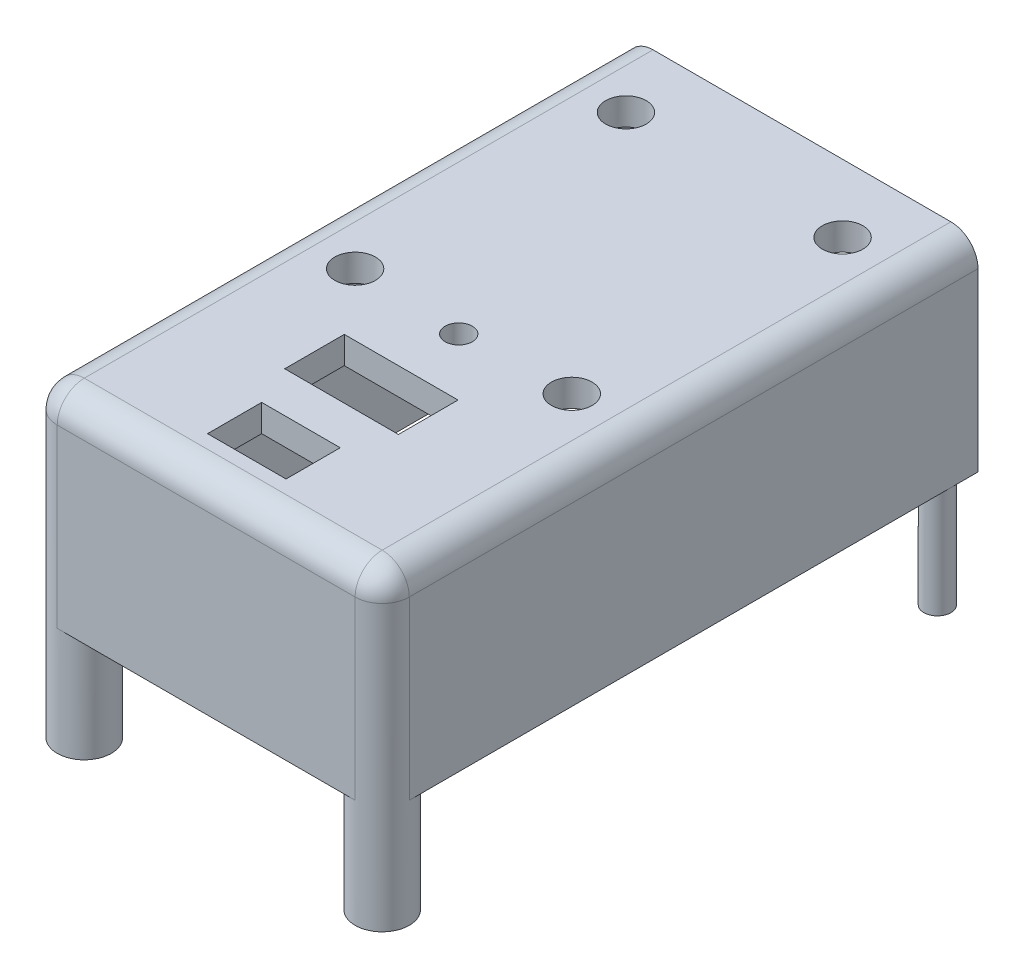
SolidWorks part; units mm, degrees
ref_plane "Front Plane" through (0, 0, 0) normal (0, 0, 1) x (1, 0, 0)
ref_plane "Top Plane" through (0, 0, 0) normal (0, 1, 0) x (1, 0, 0)
ref_plane "Right Plane" through (0, 0, 0) normal (1, 0, 0) x (0, 0, -1)
sketch "Sketch1" plane through (0, 0, 0) normal (0, 1, 0) x (1, 0, 0)
  line L1 (0, 0) -> (33.02, 0)
  line L2 (0, 0) -> (0, 55.88)
  line L3 (0, 55.88) -> (33.02, 55.88)
  line L4 (33.02, 0) -> (33.02, 55.88)
  dimension "D1" = 55.88
  dimension "D2" = 33.02
extrude "Boss-Extrude1" add sketch "Sketch1" along normal blind 19.05
shell "Shell2" thickness 2.54
fillet "Fillet2" radius 2.54 5 edges at (0, 9.525, 0) (0, 19.05, -27.94) (33.02, 19.05, -27.94) (16.51, 19.05, 0) (33.02, 9.525, 0)
sketch "Sketch2" plane through (0, 19.05, 0) normal (0, 1, 0) x (1, 0, 0)
  line L0 (30.48, 55.88) -> (2.54, 55.88) construction
  line L1 (30.48, 55.88) -> (2.54, 55.88) construction
  line L3 (33.02, 55.88) -> (33.02, 2.54) construction
  line L4 (0, 2.54) -> (0, 55.88) construction
  circle A0 centre (26.67, 49.53) radius 1.905
  circle A1 centre (26.67, 24.13) radius 1.905
  circle A2 centre (6.35, 24.13) radius 1.905
  circle A3 centre (6.35, 49.53) radius 1.905
  point P2 (0, 0)
  dimension "D1" = 3.81
  dimension "D2" = 6.35
  dimension "D3" = 6.35
  dimension "D6" = 6.35
  dimension "D7" = 6.35
  dimension "D4" = 2
  dimension "D5" = 2
extrude "Cut-Extrude1" cut sketch "Sketch2" against normal up to surface (2.54 mm away) up to face at (16.51, 16.51, -29.21)
sketch "Sketch3" plane through (0, 19.05, 0) normal (0, 1, 0) x (1, 0, 0)
  line L0 (0, 0) -> (33.02, 0) construction
  line L1 (21.844, 18.288) -> (11.176, 18.288)
  line L2 (21.844, 18.288) -> (21.844, 12.7)
  line L3 (21.844, 12.7) -> (11.176, 12.7)
  line L4 (11.176, 18.288) -> (11.176, 12.7)
  point P4 (16.51, 12.7)
  point P7 (16.51, 0)
  dimension "D1" = 10.668
  dimension "D2" = 5.588
  dimension "D3" = 12.7
extrude "Cut-Extrude2" cut sketch "Sketch3" against normal up to next
sketch "Sketch4" plane through (0, 19.05, 0) normal (0, 1, 0) x (1, 0, 0)
  line L0 (0, 0) -> (33.02, 0) construction
  line L2 (11.176, 12.7) -> (21.844, 12.7) construction
  circle A0 centre (16.51, 23.688) radius 1.27
  point P2 (16.51, 22.5683)
  point P5 (16.51, 0)
  dimension "D1" = 2.54
  dimension "D2" = 9.8683
  dimension "D3" = 10.988
extrude "Cut-Extrude3" cut sketch "Sketch4" against normal up to next
sketch "Sketch5" plane through (0, 19.05, 0) normal (0, 1, 0) x (1, 0, 0)
  line L1 (20.193, 8.89) -> (12.827, 8.89)
  line L2 (20.193, 8.89) -> (20.193, 3.81)
  line L3 (20.193, 3.81) -> (12.827, 3.81)
  line L4 (12.827, 8.89) -> (12.827, 3.81)
  line L6 (0, 0) -> (33.02, 0) construction
  line L7 (11.176, 12.7) -> (21.844, 12.7) construction
  point P4 (16.51, 3.81)
  point P8 (16.51, 0)
  dimension "D1" = 5.08
  dimension "D2" = 7.366
  dimension "D3" = 3.81
extrude "Cut-Extrude4" cut sketch "Sketch5" against normal up to next
sketch "Sketch6" plane through (0, 0, 0) normal (0, -1, 0) x (-1, 0, 0)
  line L0 (-33.02, 2.54) -> (-33.02, 55.88) construction
  line L1 (0, 55.88) -> (0, 2.54) construction
  line L2 (-2.54, 55.88) -> (0, 55.88) construction
  circle A0 centre (-30.48, 2.54) radius 2.54
  circle A2 centre (-2.54, 2.54) radius 2.54
  circle A4 centre (-31.75, 53.34) radius 1.27
  circle A6 centre (-1.27, 53.34) radius 1.27
  dimension "D2" = 2.54
  dimension "D3" = 5.08
  dimension "D1" = 1.27
  dimension "D4" = 1.27
  dimension "D5" = 2.54
  dimension "D6" = 27.94
  dimension "D7" = 50.8
  dimension "D8" = 30.48
extrude "Boss-Extrude2" add sketch "Sketch6" along normal blind 10.16 and the other way up to surface
hole_wizard "#49 (0.073) Diameter Hole1" positions "Sketch11" profile "Sketch8" hole size "#49" standard "ANSI Inch"
sketch "Sketch11" plane through (0, 0, -55.88) normal (0, 0, -1) x (-1, 0, 0)
  line L0 (-33.02, 16.51) -> (-33.02, 0) construction
  line L2 (0, 16.51) -> (0, 0) construction
  line L3 (-33.02, 0) -> (-30.48, 0) construction
  line L4 (-2.54, 0) -> (0, 0) construction
  point P0 (-31.75, 15.24)
  point P2 (-31.75, 2.54)
  point P4 (-1.27, 2.54)
  point P6 (-1.27, 15.24)
  point P17 (-31.75, 2.1704)
  point P18 (0, 0)
  point P19 (0, 0)
  dimension "D1" = 1.27
  dimension "D2" = 1.27
  dimension "D3" = 12.7
  dimension "D4" = 1.27
  dimension "D5" = 1.27
  dimension "D6" = 12.7
  dimension "D7" = 2.54
  dimension "D8" = 2.54
sketch "Sketch8" plane through (31.75, 15.24, -55.88) normal (1, 0, 0) x (0, 1, 0)
  line L0 (0, 0) -> (0, 9.4471)
  line L1 (0, 9.4471) -> (0.9271, 8.89)
  line L2 (0.9271, 8.89) -> (0.9271, 0)
  line L5 (0.9271, 0) -> (0, 0)
  line L10 (0, 9.4471) -> (-0.9271, 8.89) construction
  line L11 (0, -6.35) -> (0, 107.95) construction
  dimension "Hole Dia." = 1.8542
  dimension "Hole Depth" = 8.89
  dimension "Drill Angle" = 118
